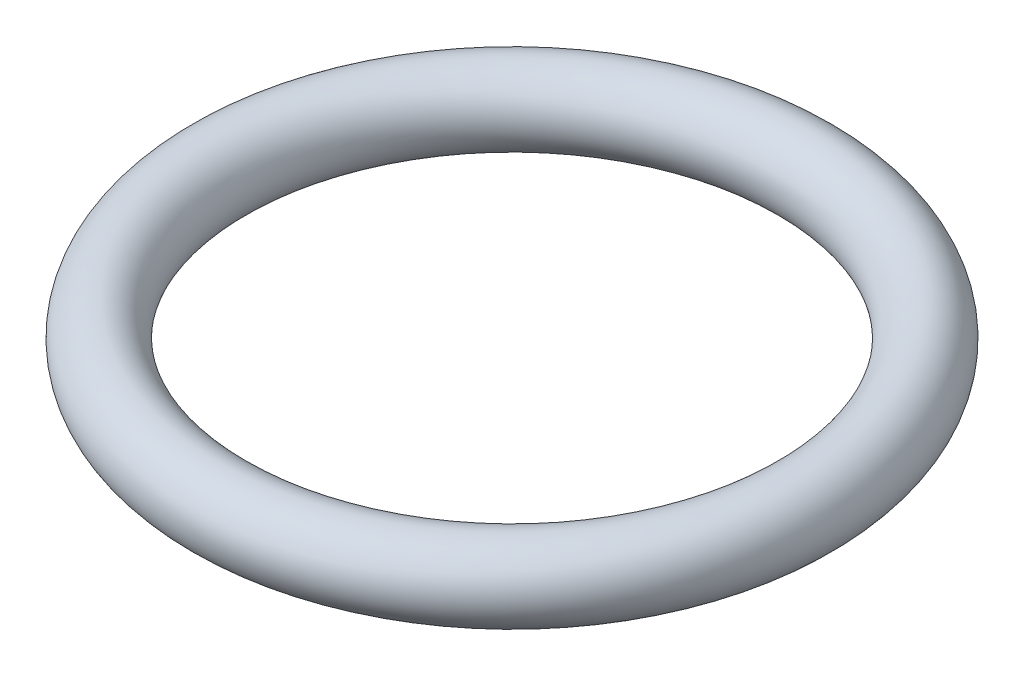
SolidWorks part; units mm, degrees
ref_plane "Front Plane" through (0, 0, 0) normal (0, 0, 1) x (1, 0, 0)
ref_plane "Top Plane" through (0, 0, 0) normal (0, 1, 0) x (1, 0, 0)
ref_plane "Right Plane" through (0, 0, 0) normal (1, 0, 0) x (0, 0, -1)
sketch "Sketch5" plane through (0, 0, 0) normal (0, 0, 1) x (1, 0, 0)
  line L0 (0, 0) -> (5.875, 0) construction
  line L1 (5.875, 0) -> (5.875, 12.9323) construction
  circle A0 centre (0, 0) radius 0.75
  dimension "D1" = 1.5
  dimension "D2" = 5.875
revolve "Revolve1" add sketch "Sketch5" angle 360 about L1
